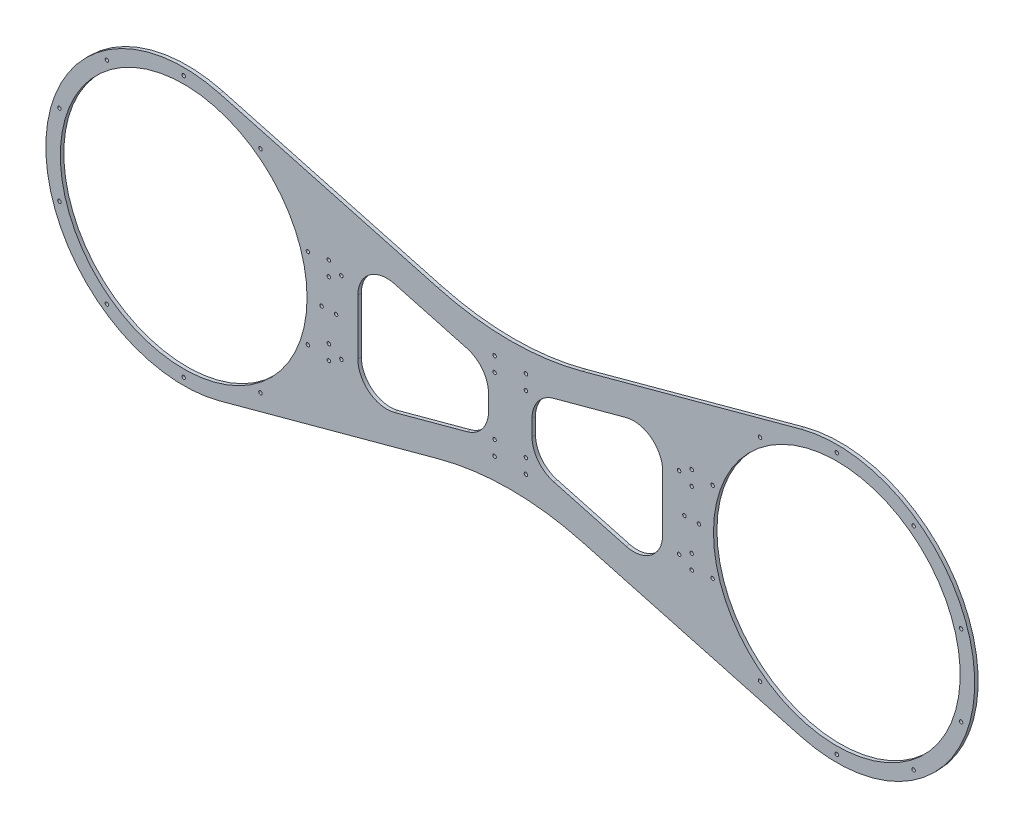
SolidWorks part; units mm, degrees
ref_plane "Front Plane" through (0, 0, 0) normal (0, 0, 1) x (1, 0, 0)
ref_plane "Top Plane" through (0, 0, 0) normal (0, 1, 0) x (1, 0, 0)
ref_plane "Right Plane" through (0, 0, 0) normal (1, 0, 0) x (0, 0, -1)
sketch "Sketch1" plane through (0, 0, 0) normal (0, 0, 1) x (1, 0, 0)
  line L0 (0, 0) -> (0, 959.0652) construction
  line L1 (-75, 104.2062) -> (-75, -104.2062)
  line L2 (-1125, 0) -> (0, 0) construction
  line L3 (-75, -104.2062) -> (-525, -226.0475)
  line L4 (-1000.8596, 458.4912) -> (0, 187.5)
  line L5 (-1000.8596, -458.4912) -> (0, -187.5)
  line L6 (0, -187.5) -> (0, 187.5)
  line L7 (-625, 356.724) -> (-625, -356.724) construction
  line L8 (-525, -226.0475) -> (-525, 226.0475)
  line L9 (-525, 226.0475) -> (-75, 104.2062)
  line L10 (-54, 202.121) -> (-54, -202.121) construction
  circle A0 centre (-1125, 0) radius 425
  arc A1 (-1000.8596, 458.4912) -> (-1000.8596, -458.4912) centre (-1125, 0) ccw
  circle A2 centre (-1125, 0) radius 450 construction
  circle A3 centre (-1125, 450) radius 6
  circle A4 centre (-860.4966, 364.0576) radius 6
  circle A5 centre (-697.0246, 139.0576) radius 6
  circle A6 centre (-697.0246, -139.0576) radius 6
  circle A7 centre (-860.4966, -364.0576) radius 6
  circle A8 centre (-1125, -450) radius 6
  circle A9 centre (-1389.5034, -364.0576) radius 6
  circle A10 centre (-1552.9754, -139.0576) radius 6
  circle A11 centre (-1552.9754, 139.0576) radius 6
  circle A12 centre (-1389.5034, 364.0576) radius 6
  circle A13 centre (-625, 150) radius 6
  circle A14 centre (-625, 100) radius 6
  circle A15 centre (-581.6987, 125) radius 6
  circle A16 centre (-625, -150) radius 6
  circle A17 centre (-581.6987, -125) radius 6
  circle A18 centre (-625, -100) radius 6
  circle A19 centre (-600, 0) radius 6
  circle A20 centre (-650, 0) radius 6
  circle A21 centre (-54, 150) radius 6
  circle A22 centre (-54, 100) radius 6
  circle A23 centre (-54, -150) radius 6
  circle A24 centre (-54, -100) radius 6
  point P34 (-1125, 0)
  point P56 (-54, 125)
  dimension "D1" = 850
  dimension "D2" = 950
  dimension "D6" = 900
  dimension "D7" = 12
  dimension "D10" = 12
  dimension "D24" = 12
  dimension "D3" = 1125
  dimension "D5" = 375
  dimension "D9" = 625
  dimension "D11" = 50
  dimension "D12" = 50
  dimension "D13" = 50
  dimension "D14" = 150
  dimension "D15" = 25
  dimension "D16" = 25
  dimension "D4" = 100
  dimension "D17" = 100
  dimension "D18" = 75
  dimension "D19" = 100
  dimension "D20" = 54
  dimension "D21" = 125
  dimension "D22" = 25
  dimension "D23" = 25
  dimension "D8" = 10
extrude "Boss-Extrude1" add sketch "Sketch1" along normal blind 12
mirror "Mirror1" about plane through (0, -187.5, 12) normal (-1, 0, 0) of "Boss-Extrude1"
fillet "Fillet1" radius 950 2 edges at (0, -187.5, 6) (0, 187.5, 6)
fillet "Fillet2" radius 100 8 edges at (-75, 104.2062, 6) (-525, 226.0475, 6) (-525, -226.0475, 6) (-75, -104.2062, 6) (525, 226.0475, 6) (525, -226.0475, 6) (75, 104.2062, 6) (75, -104.2062, 6)
equation "\"mbtOD\" = 850"
equation "\"mbtT\" = 6"
equation "\"mbtL\" = 1500"
equation "\"mbtFlangeOD\" = 950"
equation "\"mbtFlangeT\" = 12"
equation "\"mbtFlangeBoltCircleDia\" = 650"
equation "\"mbtFlangeHoleDia\" = 12"
equation "\"mbtOringSize\" = 10 "
equation "\"mbtOringDia\" = 620"
equation "\"D1@Sketch1\"=\"mbtOD\""
equation "\"D2@Sketch1\"=\"mbtFlangeOD\""
equation "\"mbtWidth\" = 2250"
equation "\"D3@Sketch1\"=\"mbtWidth\"/2"
equation "\"D6@Sketch1\"=(\"mbtOD\"+\"mbtFlangeOD\")/2"
equation "\"D7@Sketch1\"=\"mbtFlangeHoleDia\""
equation "\"skiWidth\" = 1250"
equation "\"D9@Sketch1\"=\"skiWidth\"/2"
equation "\"D1@Boss-Extrude1\"=\"mbtFlangeT\""
equation "\"mbtCapL\" = 500"
equation "\"D1@Fillet1\"=\"mbtFlangeOD\""
equation "\"vbtRearOD\" = 500"
equation "\"vbtRearT\" = 6.25"
equation "\"vbtRearFlangeOD\" = 600"
equation "\"vbtRearFlangeT\" = 12"
equation "\"vbtRearBoltHoleDia\" = 12"
equation "\"vbtFrontOD\" = 440"
equation "\"vbtFrontT\" = 25"
equation "\"vbtFrontFlangeOD\" = 500"
equation "\"vbtFrontFlangeT\" = 12"
equation "\"vbtFrontBoltHoleDia\" = 12"
equation "\"D20@Sketch1\"=2*\"vbtRearFlangeT\"+30mm"
